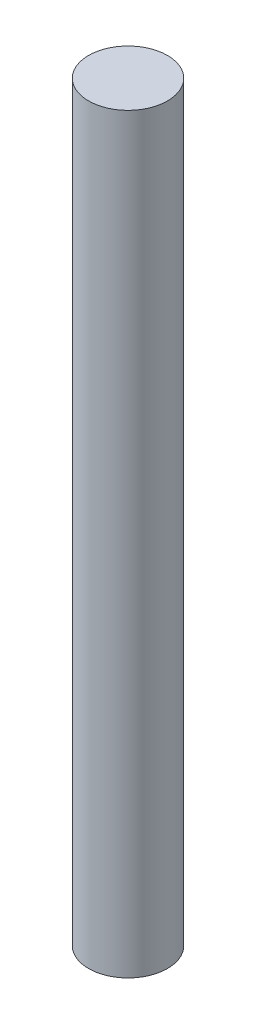
SolidWorks part; units mm, degrees
ref_plane "Front Plane" through (0, 0, 0) normal (0, 0, 1) x (1, 0, 0)
ref_plane "Top Plane" through (0, 0, 0) normal (0, 1, 0) x (1, 0, 0)
ref_plane "Right Plane" through (0, 0, 0) normal (1, 0, 0) x (0, 0, -1)
sketch "Sketch1" plane through (0, 0, 0) normal (0, 1, 0) x (1, 0, 0)
  circle A0 centre (0, 0) radius 4
  dimension "D1" = 8
extrude "Boss-Extrude1" add sketch "Sketch1" along normal blind 76.2
